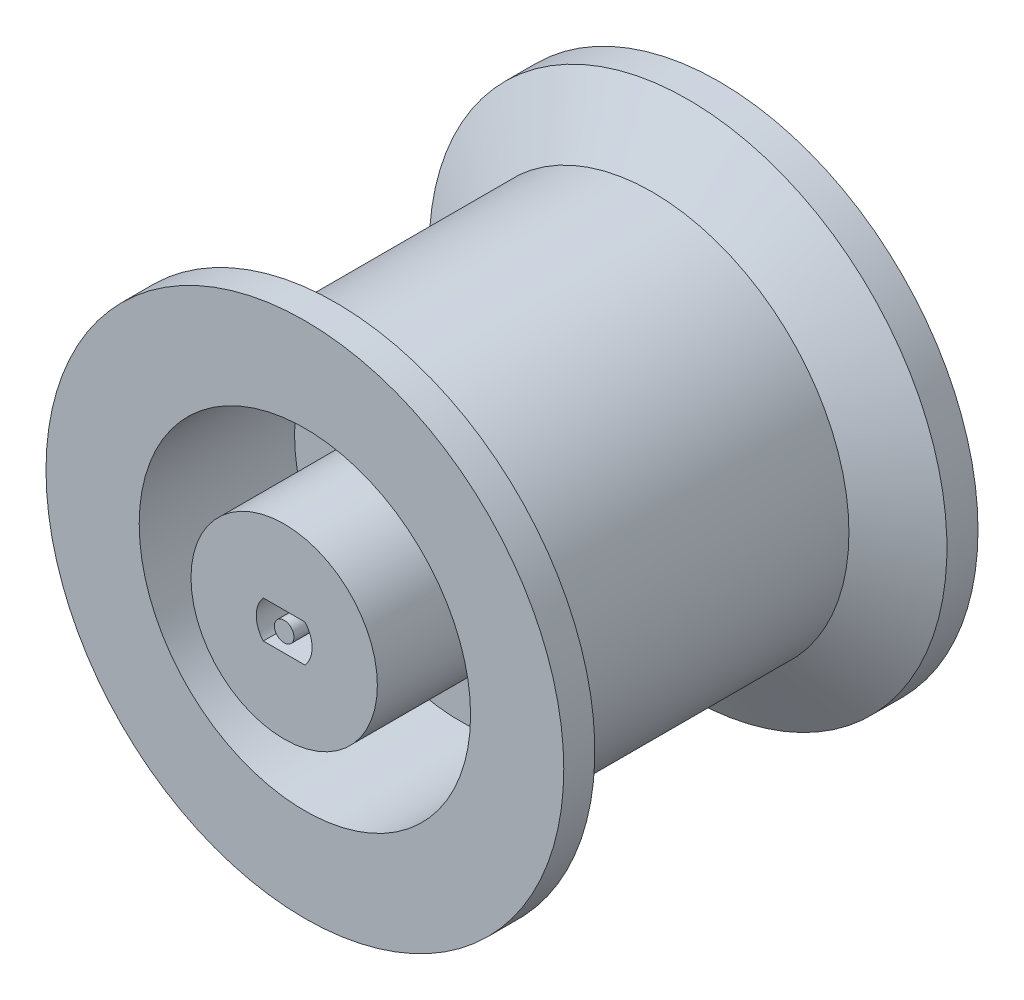
SolidWorks part; units mm, degrees
ref_plane "Plan de face" through (0, 0, 0) normal (0, 0, 1) x (1, 0, 0)
ref_plane "Plan de dessus" through (0, 0, 0) normal (0, 1, 0) x (1, 0, 0)
ref_plane "Plan de droite" through (0, 0, 0) normal (1, 0, 0) x (0, 0, -1)
sketch "Esquisse1" plane through (0, 0, 0) normal (0, 0, 1) x (1, 0, 0)
  circle A0 centre (0, 0) radius 25
  circle A1 centre (0, 0) radius 8
  dimension "D1" = 50
  dimension "D2" = 16
extrude "Boss.-Extru.1" add sketch "Esquisse1" along normal mid plane 40
sketch "Esquisse2" plane through (0, 0, 20) normal (0, 0, 1) x (1, 0, 0)
  circle A0 centre (0, 0) radius 16
  circle A1 centre (0, 0) radius 25 construction
  dimension "D1" = 9
extrude "Enlèv. mat.-Extru.1" cut sketch "Esquisse2" against normal blind 15
mirror "Symétrie1" about plane through (0, 0, 0) normal (0, 0, 1) of "Enlèv. mat.-Extru.1"
sketch "Esquisse3" plane through (0, 0, 5) normal (0, 0, 1) x (1, 0, 0)
  circle A0 centre (0, 12) radius 2.5
  dimension "D1" = 12
  dimension "D2" = 5
extrude "Enlèv. mat.-Extru.2" cut sketch "Esquisse3" against normal through all
pattern_circular "Répétition circulaire1" count 5 over 360 about axis through (0, 0, 0) along (0, 0, 1) of "Enlèv. mat.-Extru.2"
sketch "Esquisse4" plane through (0, 0, 5) normal (0, 0, 1) x (1, 0, 0)
  circle A0 centre (0, 0) radius 9
  circle A1 centre (0, 0) radius 8 construction
  circle A2 centre (0, 0) radius 8
  dimension "D1" = 18
extrude "Boss.-Extru.2" add sketch "Esquisse4" along normal blind 17 and the other way blind 12
sketch "Esquisse5" plane through (0, 0, 0) normal (0, 1, 0) x (1, 0, 0)
  line L0 (0, 25.2846) -> (0, 0) construction
  line L1 (-25, 17) -> (-19, 13.5359)
  line L2 (-25, 20) -> (-25, -20) construction
  line L3 (-19, 13.5359) -> (-19, -13.5359)
  line L4 (-19, -13.5359) -> (-25, -17)
  line L5 (-25, -17) -> (-25, 17)
  dimension "D1" = 6
  dimension "D2" = 60
  dimension "D3" = 60
  dimension "D4" = 3
  dimension "D5" = 3
revolve "Enlèvement de matière-Révolution1" cut sketch "Esquisse5" angle 360 about L0
sketch "Esquisse13" plane through (0, 0, 22) normal (0, 0, 1) x (1, 0, 0)
  circle A0 centre (0, 0) radius 8 construction
  circle A1 centre (0, 0) radius 8
extrude "Boss.-Extru.7" add sketch "Esquisse13" against normal up to surface (29 mm away) up to face at (8, 0, -7)
sketch "Esquisse11" plane through (0, 0, 22) normal (0, 0, 1) x (1, 0, 0)
  line L1 (-2.015, 1.8) -> (2.015, 1.8)
  line L2 (-2.015, -1.8) -> (2.015, -1.8)
  arc A2 (-2.015, 1.8) -> (-2.015, -1.8) centre (0.0242, 0) ccw
  arc A3 (2.015, 1.8) -> (2.015, -1.8) centre (-0.0242, 0) cw
  point P2 (0, 0)
  dimension "D2" = 3.6
  dimension "D4" = 2.72
  dimension "D1" = 4.03
  dimension "D3" = 1.8
extrude "Enlèv. mat.-Extru.3" cut sketch "Esquisse11" against normal blind 7.7
sketch "Esquisse12" plane through (0, 0, 14.3) normal (0, 0, 1) x (1, 0, 0)
  circle A0 centre (0, 0) radius 0.945
  dimension "D1" = 1.89
extrude "Boss.-Extru.6" add sketch "Esquisse12" along normal up to surface (7.7 mm away) up to face at (0, 0, 22)
